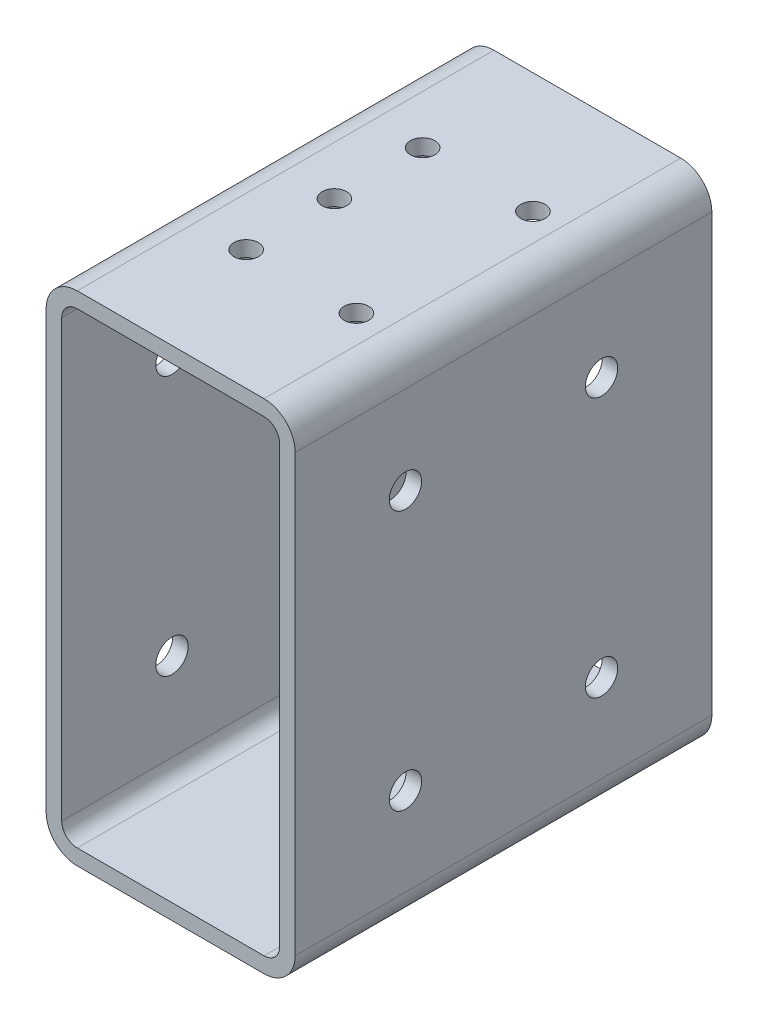
SolidWorks part; units mm, degrees
material "Plain Carbon Steel"
ref_plane "Front Plane" through (0, 0, 0) normal (0, 0, 1) x (1, 0, 0)
ref_plane "Top Plane" through (0, 0, 0) normal (0, 1, 0) x (1, 0, 0)
ref_plane "Right Plane" through (0, 0, 0) normal (1, 0, 0) x (0, 0, -1)
sketch "Sketch4" plane through (0, 0, 0) normal (1, 0, 0) x (0, 0, -1)
  line L0 (-42.5, 0) -> (42.5, 0)
  dimension "D1" = 85
other "Cnc 4X2X0.125(1)"
ref_plane "Plane1" through (0, 0, 42.5) normal (0, 0, -1) x (0, 1, 0)
sketch "Sketch1" plane through (0, 0, 42.5) normal (0, 0, -1) x (0, 1, 0)
  line L0 (44.45, 22.225) -> (-44.45, 22.225)
  line L1 (44.45, -25.4) -> (-44.45, -25.4)
  line L2 (50.8, -19.05) -> (50.8, 19.05)
  line L3 (44.45, 25.4) -> (-44.45, 25.4)
  line L4 (-50.8, -19.05) -> (-50.8, 19.05)
  line L5 (50.8, -25.4) -> (-50.8, 25.4) construction
  line L6 (50.8, 25.4) -> (-50.8, -25.4) construction
  line L7 (-47.625, -19.05) -> (-47.625, 19.05)
  line L8 (44.45, -22.225) -> (-44.45, -22.225)
  line L9 (47.625, -19.05) -> (47.625, 19.05)
  line L10 (50.8, -25.4) -> (-50.8, -25.4) construction
  line L11 (-50.8, -25.4) -> (-50.8, 25.4) construction
  line L12 (50.8, -25.4) -> (50.8, 25.4) construction
  line L13 (50.8, 25.4) -> (-50.8, 25.4) construction
  line L14 (-47.625, -22.225) -> (-47.625, 22.225) construction
  line L15 (47.625, -22.225) -> (-47.625, -22.225) construction
  line L16 (47.625, -22.225) -> (47.625, 22.225) construction
  line L17 (47.625, 22.225) -> (-47.625, 22.225) construction
  arc A0 (-44.45, -25.4) -> (-50.8, -19.05) centre (-44.45, -19.05) cw
  arc A1 (44.45, -25.4) -> (50.8, -19.05) centre (44.45, -19.05) ccw
  arc A2 (50.8, 19.05) -> (44.45, 25.4) centre (44.45, 19.05) ccw
  arc A3 (-44.45, 25.4) -> (-50.8, 19.05) centre (-44.45, 19.05) ccw
  arc A4 (-47.625, -19.05) -> (-44.45, -22.225) centre (-44.45, -19.05) ccw
  arc A5 (44.45, -22.225) -> (47.625, -19.05) centre (44.45, -19.05) ccw
  arc A6 (44.45, 22.225) -> (47.625, 19.05) centre (44.45, 19.05) cw
  arc A7 (-44.45, 22.225) -> (-47.625, 19.05) centre (-44.45, 19.05) ccw
  point P0 (0, 0)
  point P34 (0, 0)
  dimension "D4" = 6.35
  dimension "D5" = 3.175
  dimension "D1" = 101.6
  dimension "D2" = 50.8
  dimension "D3" = 3.175
sketch "Sketch3" plane through (0, 50.8, 0) normal (0, 1, 0) x (1, 0, 0)
  line L0 (-24.6642, 0) -> (5.453, 0) construction
  line L1 (-9.1, 18) -> (-9.1, -18) construction
  line L2 (-9.1, 18) -> (13.4, 18) construction
  line L3 (13.4, 18) -> (13.4, -18) construction
  line L5 (25.4, 42.5) -> (25.4, -42.5) construction
  circle A0 centre (-9.1, 18) radius 2.5
  circle A1 centre (-9.1, 0) radius 2.5
  circle A2 centre (-9.1, -18) radius 2.5
  circle A3 centre (13.4, 18) radius 2.5
  circle A4 centre (13.4, -18) radius 2.5
  point P5 (-9.1, 0)
  dimension "D2" = 5
  dimension "D1" = 36
  dimension "D3" = 22.5
  dimension "D4" = 12
sketch "Sketch2" plane through (25.4, 0, 0) normal (1, 0, 0) x (0, 0, -1)
  line L1 (20, 26.5) -> (-20, 26.5) construction
  line L2 (20, 26.5) -> (20, -26.5) construction
  line L3 (20, -26.5) -> (-20, -26.5) construction
  line L4 (-20, 26.5) -> (-20, -26.5) construction
  line L5 (20, 26.5) -> (-20, -26.5) construction
  line L6 (20, -26.5) -> (-20, 26.5) construction
  circle A0 centre (-20, 26.5) radius 3.3
  circle A1 centre (20, 26.5) radius 3.3
  circle A2 centre (20, -26.5) radius 3.3
  circle A3 centre (-20, -26.5) radius 3.3
  point P0 (0, 0)
  dimension "D3" = 6.6
  dimension "D1" = 53
  dimension "D2" = 40
extrude "Cut-Extrude1" cut sketch "Sketch3" against normal blind 10
extrude "Cut-Extrude2" cut sketch "Sketch2" against normal through all
equation "\"M5_tap\"=4.2mm\t\t\t\t\t\t\t' Below you can do mesurements as follows: cm, mm, ft, in, m, "
equation "\"M5_clearence\"=5.5mm"
equation "\"M6_tap\"=5mm"
equation "\"M6_clearence\"=6.6mm"
equation "\"work_area_width\"=1100mm"
equation "\"work_area_depth\"=900mm"
equation "\"steel_base_width\"=3in\t"
equation "\"steel_base_height\"=2in"
equation "\"steel_base_wall_thickness\"=0.125in"
equation "\"steel_base_radius\"=6mm"
equation "\"steel_sides_width\"=3in\t\t\t\t\t'this tube is rotated so flip width/height"
equation "\"steel_sides_height\"=2in\t\t\t\t'this tube is rotated so flip width/height"
equation "\"steel_sides_wall_thickness\"=0.125in"
equation "\"steel_sides_radius\"=6mm"
equation "\"steel_gantry_width\"=4in\t\t\t\t'this tube is rotated so flip width/height"
equation "\"steel_gantry_height\"=3in\t\t\t\t'this tube is rotated so flip width/height"
equation "\"steel_gantry_wall_thickness\"=0.125in"
equation "\"steel_gantry_radius\"=6mm"
equation "\"D3@Sketch2\"=\"M6_clearence\""
equation "\"D2@Sketch3\"=\"M6_tap\""
equation "\"steel_rollers_width\"=3in"
equation "\"steel_rollers_height\"=2in\t\t\t\t'keep as low as possible as this increases how big plastic parts are"
equation "\"steel_rollers_wall_thickness\"=0.125in"
equation "\"steel_rollers_radius\"=6mm"
equation "\"steel_zbox_width\"=4in\t\t\t\t\t'if the gantry height (rotated) is too thick, a wider zbox is necessary"
equation "\"steel_zbox_height\"=2in\t\t\t\t\t'hole patteren changes as the zbox and gantry height (rotated) changes."
equation "\"steel_zbox_wall_thickness\"=0.125in"
equation "\"steel_zbox_radius\"=6mm"
equation "\"D1@Sketch4\"= 100mm - 7.5 * 2"
equation "\"D2@Sketch1\"=\"profile_heigth\""
equation "\"D1@Sketch1\"=\"profile_width\""
equation "\"D3@Sketch1\"=\"profile_wall\""
equation "\"D5@Sketch1\"=\"profile_wall\""
equation "\"D4@Sketch1\"=\"profile_wall\"*2"
